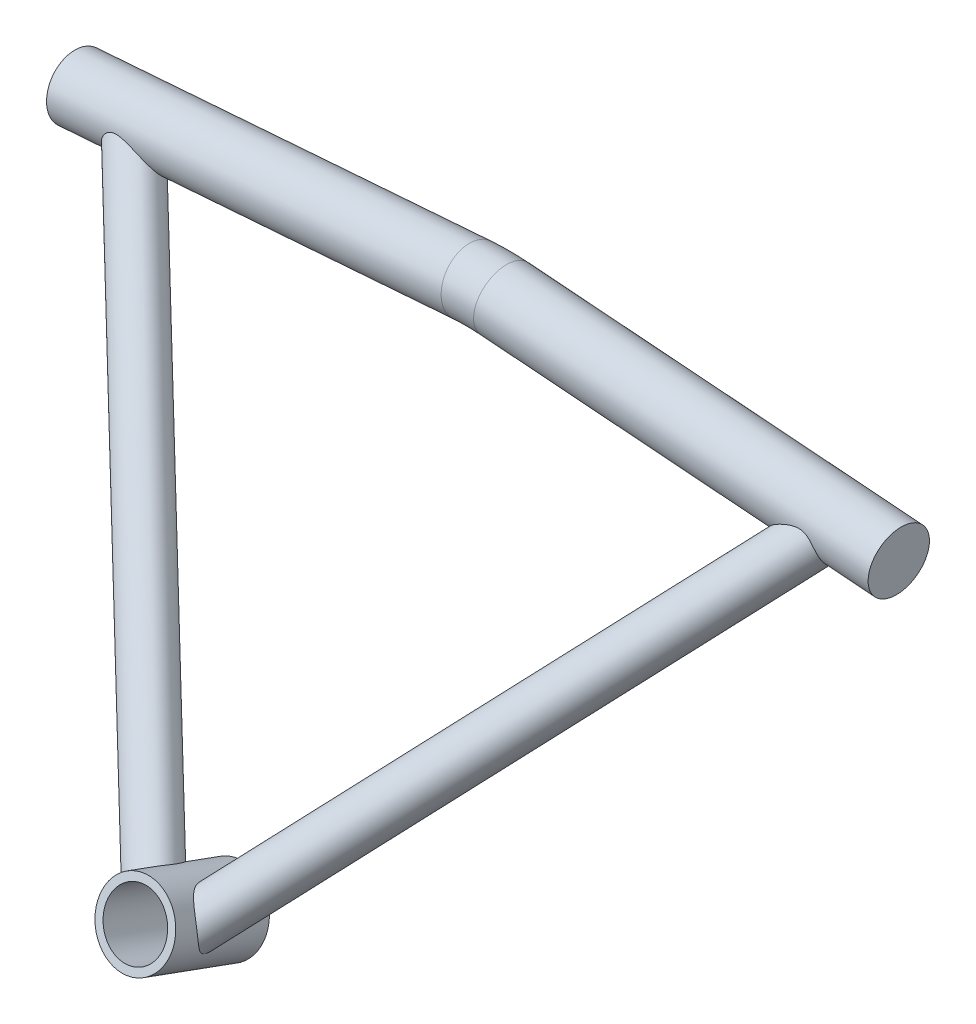
SolidWorks part; units mm, degrees
material "AISI 4130 Steel, normalized at 870C"
ref_plane "Front Plane" through (0, 0, 0) normal (0, 0, 1) x (1, 0, 0)
ref_plane "Top Plane" through (0, 0, 0) normal (0, 1, 0) x (1, 0, 0)
ref_plane "Right Plane" through (0, 0, 0) normal (1, 0, 0) x (0, 0, -1)
sketch "Sketch3" plane through (0, 0, 0) normal (0, 1, 0) x (1, 0, 0)
  line L0 (-5.08, -6.35) -> (5.08, -6.35) construction
  line L2 (0, -88.2205) -> (0, 88.2205) construction
  line L3 (5.08, 0) -> (-5.08, 0) construction
  dimension "D1" = 5.08
  dimension "D2" = 10.16
  dimension "D3" = 6.35
  dimension "D4" = 10.16
  dimension "D5" = 5.08
ref_plane "Plane1" through (0, 3.1441, 3.6169) normal (0, 0.6561, 0.7547) x (1, 0, 0)
ref_plane "Plane3" through (0, 0, 0) normal (0, 0.342, 0.9397) x (-1, 0, 0)
sketch "Sketch1" plane through (0, 0, 0) normal (0, 0.342, 0.9397) x (1, 0, 0)
  circle A0 centre (0, 0) radius 15.875
  dimension "D1" = 31.75
extrude "Boss-Extrude1" add sketch "Sketch1" along normal mid plane 41.402 contours A0
sketch "Sketch4" plane through (0, 3.1441, 3.6169) normal (0, 0.6561, 0.7547) x (1, 0, 0)
  line L0 (-5.08, -4.166) -> (-143.484, 193.4954)
  line L2 (0, -90.5202) -> (0, 90.5202) construction
  dimension "D2" = 35
  dimension "D3" = 241.3
sweep "Sweep1" add path "Sketch4" circular profile diameter 19.05 parameters "D3"=19.05
sketch "Sketch15" plane through (0, 3.1441, 3.6169) normal (0, 0.6561, 0.7547) x (1, 0, 0)
  line L0 (5.08, -4.166) -> (143.484, 193.4954)
  line L1 (0, -90.5202) -> (0, 90.5202) construction
  dimension "D1" = 241.3
  dimension "D2" = 35
sweep "Sweep2" add path "Sketch15" circular profile diameter 19.05 parameters "D3"=19.05
sketch "Sketch36" plane through (-138.1179, 148.8686, -129.4095) normal (-0.5736, 0.6182, -0.5374) x (0.8191, 0.4394, -0.3687)
  circle A0 centre (-6.5024, -4.8578) radius 7.9375
  dimension "D1" = 15.875
extrude "Cut-Extrude2" cut sketch "Sketch36" against normal up to surface (251.5099 mm away)
sketch "Sketch37" plane through (138.1179, 148.8686, -129.4095) normal (0.5736, 0.6182, -0.5374) x (0.8191, -0.4394, 0.3687)
  circle A0 centre (6.5024, -4.8578) radius 7.9375
  dimension "D1" = 15.875
extrude "Cut-Extrude3" cut sketch "Sketch37" against normal up to surface (226.8376 mm away)
sketch "Sketch77" plane through (0, 7.0802, 19.4526) normal (0, 0.342, 0.9397) x (1, 0, 0)
  circle A1 centre (0, 0) radius 15.875
extrude "Boss-Extrude2" add sketch "Sketch77" against normal up to surface (41.402 mm away) up to face at (0, -21.9978, -14.023)
sketch "Sketch2" plane through (0, -7.0802, -19.4526) normal (0, -0.342, -0.9397) x (-1, 0, 0)
  circle A0 centre (0, 0) radius 12.7
  dimension "D1" = 25.4
extrude "Cut-Extrude1" cut sketch "Sketch2" against normal up to next
ref_plane "Plane2" through (0, 0, -127) normal (0, 0, 1) x (1, 0, 0)
sketch "Sketch40" plane through (-106.934, 0, -127) normal (0, 0, 1) x (1, 0, 0)
  line L2 (106.934, -85.9333) -> (106.934, 85.9333) construction
  line L3 (100.2024, 162.3048) -> (-63.6638, 149.8608)
  line L4 (113.6656, 162.3048) -> (277.5318, 149.8608)
  arc A0 (100.2024, 162.3048) -> (113.6656, 162.3048) centre (106.934, 73.66) cw
  point P0 (106.934, 162.56)
  point P7 (106.934, 162.56)
  dimension "D1" = 164.338
  dimension "D3" = 88.9
  dimension "D2" = 164.338
  dimension "D4" = 4.75
sweep "Sweep3" add path "Sketch40" circular profile diameter 25.4 parameters "D3"=25.4
